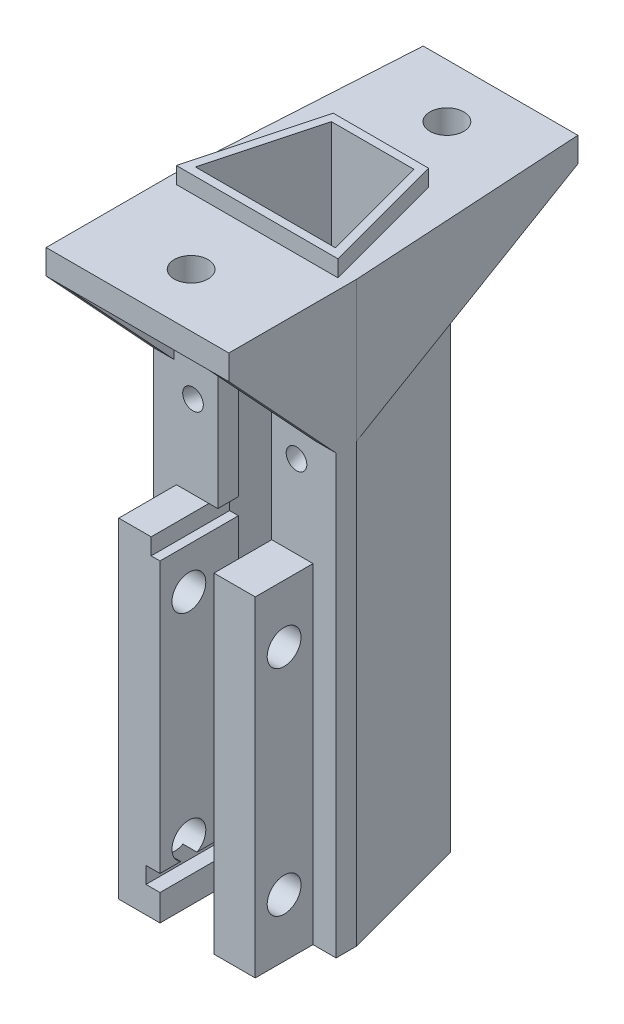
SolidWorks part; units mm, degrees
ref_plane "Front Plane" through (0, 0, 0) normal (0, 0, 1) x (1, 0, 0)
ref_plane "Top Plane" through (0, 0, 0) normal (0, 1, 0) x (1, 0, 0)
ref_plane "Right Plane" through (0, 0, 0) normal (1, 0, 0) x (0, 0, -1)
sketch "Sketch2" plane through (0, 0, 0) normal (0, 1, 0) x (1, 0, 0)
  line L0 (-8.0683, 3.8436) -> (5.7683, 3.8436)
  line L1 (-8.0683, 3.8436) -> (-8.0683, 1.3436)
  line L2 (5.7683, 3.8436) -> (5.7683, 1.3436)
  line L3 (-8.0683, 1.3436) -> (5.7683, 1.3436)
  line L4 (5.7683, 3.8436) -> (9.9215, -11.6564)
  line L5 (5.7683, 3.8436) -> (3.3535, 3.1965)
  line L6 (9.9215, -11.6564) -> (7.5067, -12.3035)
  line L7 (3.3535, 3.1965) -> (7.5067, -12.3035)
  line L8 (-8.0683, 3.8436) -> (-12.2215, -11.6564)
  line L9 (-8.0683, 3.8436) -> (-5.6535, 3.1965)
  line L10 (-12.2215, -11.6564) -> (-9.8067, -12.3035)
  line L11 (-5.6535, 3.1965) -> (-9.8067, -12.3035)
  line L12 (-12.2215, -11.6564) -> (-4.4215, -11.6564)
  line L13 (-12.2215, -11.6564) -> (-12.2215, -14.1564)
  line L14 (-4.4215, -11.6564) -> (-4.4215, -14.1564)
  line L15 (-12.2215, -14.1564) -> (-4.4215, -14.1564)
  line L16 (9.9215, -11.6564) -> (2.1215, -11.6564)
  line L17 (9.9215, -11.6564) -> (9.9215, -14.1564)
  line L18 (2.1215, -11.6564) -> (2.1215, -14.1564)
  line L19 (9.9215, -14.1564) -> (2.1215, -14.1564)
  line L20 (-4.4215, -14.1564) -> (-9.4215, -14.1564)
  line L21 (-4.4215, -14.1564) -> (-4.4215, -21.1564)
  line L22 (-9.4215, -14.1564) -> (-9.4215, -21.1564)
  line L23 (-4.4215, -21.1564) -> (-9.4215, -21.1564)
  line L24 (2.1215, -14.1564) -> (7.1215, -14.1564)
  line L25 (2.1215, -14.1564) -> (2.1215, -21.1564)
  line L26 (7.1215, -14.1564) -> (7.1215, -21.1564)
  line L27 (2.1215, -21.1564) -> (7.1215, -21.1564)
  point P0 (-6.15, 1.3436)
  point P21 (3.85, 1.3436)
  point P24 (7.3334, -11.6564)
  point P25 (-9.6333, -11.6564)
  dimension "D1" = 0
  dimension "D2" = 2.5
  dimension "D3" = 2.5
  dimension "D4" = 2.5
  dimension "D5" = 10
  dimension "D6" = 360
  dimension "D7" = 13
  dimension "D8" = 2.5
  dimension "D9" = 2.5
  dimension "D10" = 13
  dimension "D11" = 5
  dimension "D12" = 5
  dimension "D13" = 105
  dimension "D14" = 7.8
  dimension "D15" = 7.8
  dimension "D16" = 105
  dimension "D17" = 16.9667
  dimension "D18" = 6.5431
  dimension "D19" = 7
  dimension "D20" = 7
extrude "Boss-Extrude1" add sketch "Sketch2" along normal blind 40 contours L16 L4 L2 L3 L7 | L9 L11 L3 L7 L5 L0 | L8 L12 L11 L3 L1 | L5 L7 L3 L2 | L11 L9 L1 L3 | L13 L15 L14 L12 L11 L10 | L12 L10 L11 | L6 L16 L7 | L19 L17 L6 L7 L16 L18 | L25 L27 L26 L19 | L23 L21 L15 L22
sketch "Sketch3" plane through (-9.4215, 0, 0) normal (-1, 0, 0) x (0, 0, 1)
  line L0 (21.1564, 40) -> (21.1564, 0) construction
  line L1 (14.1564, 40) -> (14.1564, 0) construction
  line L2 (14.1564, 40) -> (21.1564, 40) construction
  line L3 (14.1564, 0) -> (21.1564, 0) construction
  circle A0 centre (17.6564, 33) radius 2.05
  circle A1 centre (17.6564, 7) radius 2.05
  dimension "D5" = 4.1
  dimension "D6" = 4.1
  dimension "D1" = 3.5
  dimension "D2" = 3.5
  dimension "D3" = 3.5
  dimension "D4" = 3.5
  dimension "D7" = 7
  dimension "D8" = 7
extrude "Cut-Extrude2" cut sketch "Sketch3" against normal blind 40
sketch "Sketch4" plane through (0, 40, 0) normal (0, 1, 0) x (1, 0, 0)
  line L0 (-9.6333, -11.6564) -> (-6.15, 1.3436)
  line L1 (-6.15, 1.3436) -> (3.85, 1.3436)
  line L2 (3.85, 1.3436) -> (7.3334, -11.6564)
  line L3 (7.3334, -11.6564) -> (2.1215, -11.6564)
  line L4 (2.1215, -11.6564) -> (2.1215, -14.1564)
  line L5 (2.1215, -11.6564) -> (2.1215, -21.1564) construction
  line L6 (2.1215, -14.1564) -> (9.9215, -14.1564)
  line L7 (9.9215, -14.1564) -> (9.9215, -11.6564)
  line L8 (9.9215, -11.6564) -> (5.7683, 3.8436)
  line L9 (5.7683, 3.8436) -> (-8.0683, 3.8436)
  line L10 (-8.0683, 3.8436) -> (-12.2215, -11.6564)
  line L11 (-12.2215, -11.6564) -> (-12.2215, -14.1564)
  line L12 (-12.2215, -14.1564) -> (-4.4215, -14.1564)
  line L13 (-4.4215, -11.6564) -> (-4.4215, -21.1564) construction
  line L14 (-4.4215, -14.1564) -> (-4.4215, -11.6564)
  line L33 (-6.15, 1.3436) -> (3.85, 1.3436)
  line L34 (3.85, 1.3436) -> (7.3334, -11.6564)
  line L35 (7.3334, -11.6564) -> (2.1215, -11.6564)
  line L36 (2.1215, -11.6564) -> (2.1215, -21.1564)
  line L37 (2.1215, -21.1564) -> (7.1215, -21.1564)
  line L38 (7.1215, -21.1564) -> (7.1215, -14.1564)
  line L39 (7.1215, -14.1564) -> (9.9215, -14.1564)
  line L40 (9.9215, -14.1564) -> (9.9215, -11.6564)
  line L41 (9.9215, -11.6564) -> (5.7683, 3.8436)
  line L42 (5.7683, 3.8436) -> (-8.0683, 3.8436)
  line L43 (-8.0683, 3.8436) -> (-12.2215, -11.6564)
  line L44 (-12.2215, -11.6564) -> (-12.2215, -14.1564)
  line L45 (-12.2215, -14.1564) -> (-9.4215, -14.1564)
  line L46 (-9.4215, -14.1564) -> (-9.4215, -21.1564)
  line L47 (-9.4215, -21.1564) -> (-4.4215, -21.1564)
  line L48 (-4.4215, -21.1564) -> (-4.4215, -11.6564)
  line L49 (-4.4215, -11.6564) -> (-9.6333, -11.6564)
  line L50 (-9.6333, -11.6564) -> (-6.15, 1.3436)
  line L51 (-6.15, 1.3436) -> (3.85, 1.3436)
  line L52 (3.85, 1.3436) -> (7.3334, -11.6564)
  line L53 (7.3334, -11.6564) -> (2.1215, -11.6564)
  line L54 (2.1215, -11.6564) -> (2.1215, -21.1564)
  line L55 (2.1215, -21.1564) -> (7.1215, -21.1564)
  line L56 (7.1215, -21.1564) -> (7.1215, -14.1564)
  line L57 (7.1215, -14.1564) -> (9.9215, -14.1564)
  line L58 (9.9215, -14.1564) -> (9.9215, -11.6564)
  line L59 (9.9215, -11.6564) -> (5.7683, 3.8436)
  line L60 (5.7683, 3.8436) -> (-8.0683, 3.8436)
  line L61 (-8.0683, 3.8436) -> (-12.2215, -11.6564)
  line L62 (-12.2215, -11.6564) -> (-12.2215, -14.1564)
  line L63 (-12.2215, -14.1564) -> (-9.4215, -14.1564)
  line L64 (-9.4215, -14.1564) -> (-9.4215, -21.1564)
  line L65 (-9.4215, -21.1564) -> (-4.4215, -21.1564)
  line L66 (-4.4215, -21.1564) -> (-4.4215, -11.6564)
  line L68 (-9.6333, -11.6564) -> (-6.15, 1.3436)
  line M19 (-6.15, 1.3436) -> (3.85, 1.3436)
  line M20 (3.85, 1.3436) -> (7.3334, -11.6564)
  line M21 (7.3334, -11.6564) -> (2.1215, -11.6564)
  line M22 (2.1215, -11.6564) -> (2.1215, -21.1564)
  line M25 (7.1215, -14.1564) -> (9.9215, -14.1564)
  line M26 (9.9215, -14.1564) -> (9.9215, -11.6564)
  line M27 (9.9215, -11.6564) -> (5.7683, 3.8436)
  line M28 (5.7683, 3.8436) -> (-8.0683, 3.8436)
  line M29 (-8.0683, 3.8436) -> (-12.2215, -11.6564)
  line M30 (-12.2215, -11.6564) -> (-12.2215, -14.1564)
  line M31 (-12.2215, -14.1564) -> (-9.4215, -14.1564)
  line M34 (-4.4215, -21.1564) -> (-4.4215, -11.6564)
  line M35 (-4.4215, -11.6564) -> (-9.6333, -11.6564)
  line M36 (-9.6333, -11.6564) -> (-6.15, 1.3436)
  dimension "D1" = 0
extrude "Boss-Extrude2" add sketch "Sketch4" along normal blind 30 contours L12 L6 M31 M34 M35 M36 M19 M20 M21 M22 M25 M26 M27 M28 M29 M30
sketch "Sketch7" plane through (0, 0, -3.8436) normal (0, 0, -1) x (-1, 0, 0)
  line L0 (-5.7683, 70) -> (-5.7683, 0) construction
  line L1 (5.4917, 38) -> (0.9917, 38)
  line L2 (5.4917, 38) -> (5.4917, 40)
  line L3 (5.4917, 40) -> (0.9917, 40)
  line L4 (0.9917, 38) -> (0.9917, 40)
  line L5 (8.0683, 70) -> (8.0683, 0) construction
  line L6 (8.0683, 0) -> (-5.7683, 0) construction
  point P4 (0.9917, 39)
  dimension "D1" = 6.76
  dimension "D2" = 4.5
  dimension "D3" = 2
  dimension "D4" = 2.5766
  dimension "D5" = 38
extrude "Cut-Extrude3" cut sketch "Sketch7" against normal through all
sketch "Sketch8" plane through (0, 0, 11.6564) normal (0, 0, -1) x (-1, 0, 0)
  line L0 (4.4215, 70) -> (4.4215, 40) construction
  line L1 (6.1215, 5.2) -> (4.4215, 5.2)
  line L2 (6.1215, 5.2) -> (6.1215, 3.2)
  line L3 (6.1215, 3.2) -> (4.4215, 3.2)
  line L4 (4.4215, 5.2) -> (4.4215, 3.2)
  line L5 (9.6333, 0) -> (4.4215, 0) construction
  dimension "D1" = 2
  dimension "D2" = 1.7
  dimension "D3" = 3.2
extrude "Cut-Extrude4" cut sketch "Sketch8" against normal through all
sketch "Sketch9" plane through (0, 70, 0) normal (0, 1, 0) x (1, 0, 0)
  line L0 (2.1215, -11.6564) -> (2.1215, -12.6564)
  line L1 (2.1215, -11.6564) -> (2.1215, -14.1564) construction
  line L2 (2.1215, -11.6564) -> (7.3334, -11.6564)
  line L3 (7.3334, -11.6564) -> (3.85, 1.3436)
  line L4 (3.85, 1.3436) -> (-6.15, 1.3436)
  line L5 (-6.15, 1.3436) -> (-9.6333, -11.6564)
  line L6 (-9.6333, -11.6564) -> (-4.4215, -11.6564)
  line L7 (-4.4215, -11.6564) -> (-4.4215, -12.6564)
  line L8 (-4.4215, -14.1564) -> (-4.4215, -11.6564) construction
  line L9 (-4.4215, -12.6564) -> (-10.9365, -12.6564)
  line L10 (-10.9365, -12.6564) -> (-6.9173, 2.3436)
  line L11 (-6.9173, 2.3436) -> (4.6173, 2.3436)
  line L12 (4.6173, 2.3436) -> (8.6366, -12.6564)
  line L13 (8.6366, -12.6564) -> (2.1215, -12.6564)
  line L14 (2.1215, -12.6564) -> (-4.4215, -12.6564)
  line L15 (-4.4215, -11.6564) -> (2.1215, -11.6564)
  line M8 (-4.4215, -14.1564) -> (-4.4215, -11.6564)
  line M9 (-4.4215, -11.6564) -> (-9.6333, -11.6564)
  line M10 (-9.6333, -11.6564) -> (-6.15, 1.3436)
  line M11 (-6.15, 1.3436) -> (3.85, 1.3436)
  line M12 (3.85, 1.3436) -> (7.3334, -11.6564)
  line M13 (7.3334, -11.6564) -> (2.1215, -11.6564)
  line M14 (2.1215, -11.6564) -> (2.1215, -14.1564)
  dimension "D2" = 1
  dimension "D3" = 1
  dimension "D4" = 1
  dimension "D5" = 1
  dimension "D6" = 11.5347
extrude "Boss-Extrude3" add sketch "Sketch9" along normal blind 2 contours L13 L12 L11 L10 L9 M8 M9 M10 M11 M12 M13 M14 | L15 L14 M8 M14
sketch "Sketch10" plane through (0, 0, -3.8436) normal (0, 0, -1) x (-1, 0, 0)
  line L0 (5.4917, 40) -> (0.9917, 40)
  line L1 (5.4917, 40) -> (5.4917, 115)
  line L2 (0.9917, 40) -> (0.9917, 115)
  line L3 (5.4917, 115) -> (0.9917, 115)
  dimension "D1" = 75
extrude "Cut-Extrude5" cut sketch "Sketch10" against normal blind 1.5
sketch "Sketch13" plane through (0, 0, -2.3436) normal (0, 0, -1) x (-1, 0, 0)
  line L1 (5.4917, 40) -> (8.2917, 40)
  line L2 (5.4917, 40) -> (5.4917, 42)
  line L3 (5.4917, 42) -> (8.2917, 42)
  line L4 (8.2917, 40) -> (8.2917, 42)
  dimension "D1" = 2
  dimension "D2" = 2.8
extrude "Cut-Extrude7" cut sketch "Sketch13" along normal blind 1.5
sketch "Sketch15" plane through (0, 0, -3.8436) normal (0, 0, -1) x (-1, 0, 0)
  line L0 (8.0683, 42) -> (5.4917, 42) construction
  line L1 (8.0683, 40) -> (6.5683, 40)
  line L2 (8.0683, 40) -> (8.0683, 42)
  line L3 (8.0683, 42) -> (6.5683, 42)
  line L4 (6.5683, 40) -> (6.5683, 42)
  dimension "D1" = 1.5
extrude "Cut-Extrude8" cut sketch "Sketch15" along direction (-0.2588, 0, 0.9659) on the side against the normal blind 18.5
sketch "Sketch16" plane through (0, 0, 14.1564) normal (0, 0, 1) x (1, 0, 0)
  line L0 (-4.4215, 70) -> (-4.4215, 40) construction
  line L2 (-10.9365, 70) -> (-4.4215, 70) construction
  circle A0 centre (-7.4215, 50) radius 1.25
  dimension "D1" = 20
  dimension "D2" = 2.5
  dimension "D4" = 3
extrude "Cut-Extrude9" cut sketch "Sketch16" along direction (-0.2588, 0, 0.9659) on the side against the normal blind 3.5
sketch "Sketch17" plane through (0, 0, 14.1564) normal (0, 0, 1) x (1, 0, 0)
  line L0 (2.1215, 70) -> (2.1215, 40) construction
  line L1 (2.1215, 70) -> (9.9215, 70) construction
  circle A0 centre (5.1215, 50) radius 1.25
  dimension "D1" = 2.5
  dimension "D2" = 3
  dimension "D3" = 20
extrude "Cut-Extrude10" cut sketch "Sketch17" along direction (0.2588, 0, 0.9659) on the side against the normal blind 3.5
sketch "Sketch18" plane through (0, 0, 11.6564) normal (0, 0, -1) x (-1, 0, 0)
  line L0 (-9.9215, 70) -> (-9.9215, 0) construction
  line L1 (-9.9215, 70) -> (12.2215, 70)
  line L2 (-9.9215, 70) -> (-9.9215, 67)
  line L3 (-9.9215, 67) -> (12.2215, 67)
  line L4 (12.2215, 70) -> (12.2215, 67)
  line L5 (12.2215, 70) -> (12.2215, 42) construction
  dimension "D1" = 3
  dimension "D2" = 0
extrude "Boss-Extrude4" add sketch "Sketch18" against normal blind 15.5
sketch "Sketch19" plane through (0, 0, -3.8436) normal (0, 0, -1) x (-1, 0, 0)
  line L0 (-5.7683, 70) -> (-5.7683, 0) construction
  line L1 (8.0683, 70) -> (-5.7683, 70)
  line L2 (8.0683, 70) -> (8.0683, 67)
  line L3 (8.0683, 67) -> (-5.7683, 67)
  line L4 (-5.7683, 70) -> (-5.7683, 67)
  dimension "D1" = 3
extrude "Boss-Extrude5" add sketch "Sketch19" along normal blind 13 and the other way blind 2 contours L1 L4 L3 L2
sketch "Sketch21" plane through (-12.2215, 0, 0) normal (-1, 0, 0) x (0, 0, 1)
  line L0 (27.1564, 67) -> (14.1564, 53)
  line L1 (14.1564, 67) -> (14.1564, 0) construction
  line L2 (14.1564, 53) -> (14.1564, 67)
  line L3 (14.1564, 67) -> (27.1564, 67)
  dimension "D1" = 14
extrude "Boss-Extrude6" add sketch "Sketch21" against normal blind 2.5
sketch "Sketch22" plane through (9.9215, 0, 0) normal (1, 0, 0) x (0, 0, -1)
  line L0 (-27.1564, 67) -> (-14.1564, 67)
  line L1 (-14.1564, 67) -> (-14.1564, 53)
  line L2 (-14.1564, 67) -> (-14.1564, 0) construction
  line L3 (-14.1564, 53) -> (-27.1564, 67)
  dimension "D1" = 14
extrude "Boss-Extrude8" add sketch "Sketch22" against normal blind 2.5
sketch "Sketch23" plane through (9.9215, 0, 0) normal (1, 0, 0) x (0, 0, -1)
  line L0 (-11.6564, 70) -> (-11.6564, 53)
  line L1 (-11.6564, 70) -> (-11.6564, 0) construction
  line L2 (16.8436, 70) -> (16.8436, 67)
  line L3 (16.8436, 70) -> (-11.6564, 70)
  line L4 (16.8436, 67) -> (-11.6564, 53)
  dimension "D1" = 28.5
  dimension "D2" = 28.5
  dimension "D3" = 17
  dimension "D4" = 3
extrude "Boss-Extrude9" add sketch "Sketch23" against normal blind 4.2
sketch "Sketch24" plane through (-12.2215, 0, 0) normal (-1, 0, 0) x (0, 0, 1)
  line L0 (11.6564, 70) -> (-16.8436, 70)
  line L1 (-16.8436, 70) -> (-16.8436, 67)
  line L2 (-16.8436, 67) -> (11.6564, 53)
  line L3 (11.6564, 70) -> (11.6564, 42) construction
  line L4 (11.6564, 53) -> (11.6564, 70)
  dimension "D1" = 17
  dimension "D2" = 28.5
  dimension "D3" = 3
extrude "Boss-Extrude10" add sketch "Sketch24" against normal blind 4.2
sketch "Sketch25" plane through (0, 70, 0) normal (0, 1, 0) x (1, 0, 0)
  line L0 (-6.9173, 2.3436) -> (4.6173, 2.3436) construction
  line L1 (8.6366, -12.6564) -> (-10.9365, -12.6564) construction
  circle A0 centre (-1.15, 10.3436) radius 2.05
  circle A1 centre (-1.15, -20.6564) radius 2.05
  dimension "D1" = 4.1
  dimension "D2" = 4.1
  dimension "D3" = 8
  dimension "D4" = 8
  dimension "D5" = 9.7866
  dimension "D6" = 9.7866
  dimension "D7" = 5.7673
  dimension "D8" = 5.7673
extrude "Cut-Extrude12" cut sketch "Sketch25" against normal blind 3.5
sketch "Sketch26" plane through (0, 47.3099, 23.2399) normal (0, -0.8976, -0.4409) x (-1, 0, 0)
  line L0 (-5.7215, 12.9056) -> (-7.3334, 12.9056)
  line L1 (-7.3334, 12.9056) -> (-5.7215, 19.6076)
  line L2 (-5.7215, 19.6076) -> (-5.7215, 12.9056)
  line L3 (8.0215, 12.9056) -> (8.0215, 19.6076)
  line L4 (8.0215, 19.6076) -> (9.6333, 12.9056)
  line L5 (9.6333, 12.9056) -> (8.0215, 12.9056)
extrude "Cut-Extrude13" cut sketch "Sketch26" along direction (0, -1, 0) on the side against the normal through all
sketch "Sketch27" plane through (0, 47.3099, 23.2399) normal (0, -0.8976, -0.4409) x (-1, 0, 0)
  line L0 (12.2215, 12.9056) -> (10.5215, 44.6586)
  line L1 (12.2215, 44.6586) -> (8.0215, 44.6586) construction
  line L2 (10.5215, 44.6586) -> (12.2215, 44.6586)
  line L3 (12.2215, 44.6586) -> (12.2215, 12.9056)
  line L4 (-9.9215, 12.9056) -> (-9.9215, 44.6586)
  line L5 (-9.9215, 44.6586) -> (-8.2215, 44.6586)
  line L6 (-5.7215, 44.6586) -> (-9.9215, 44.6586) construction
  line L7 (-8.2215, 44.6586) -> (-9.9215, 12.9056)
  dimension "D1" = 2.5
  dimension "D2" = 2.5
extrude "Cut-Extrude14" cut sketch "Sketch27" along direction (0, -1, 0) on the side against the normal through all
